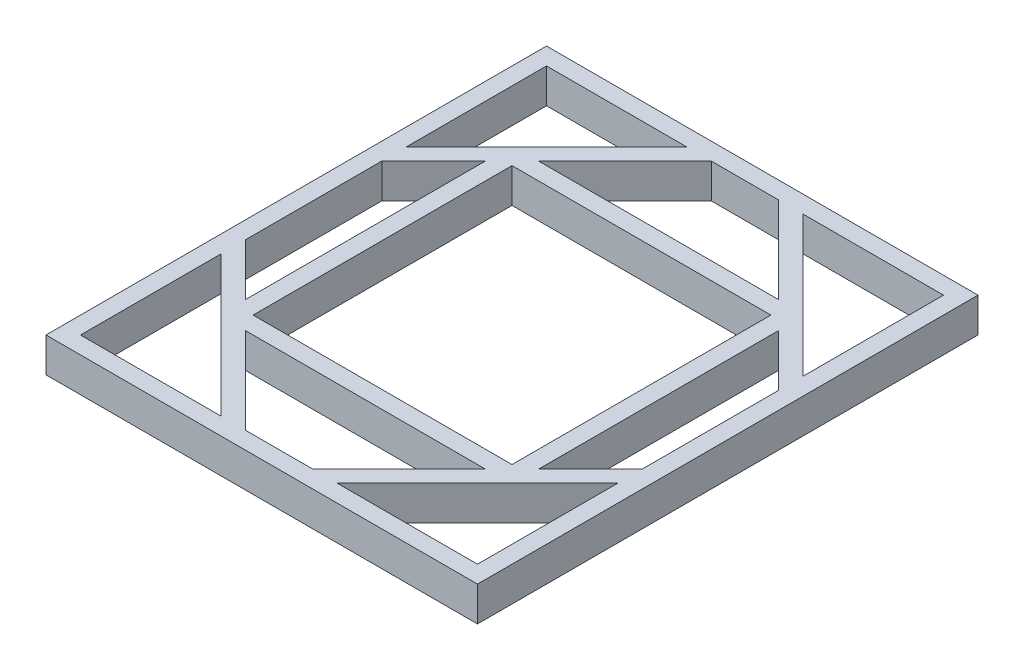
SolidWorks part; units mm, degrees
ref_plane "Front Plane" through (0, 0, 0) normal (0, 0, 1) x (1, 0, 0)
ref_plane "Top Plane" through (0, 0, 0) normal (0, 1, 0) x (1, 0, 0)
ref_plane "Right Plane" through (0, 0, 0) normal (1, 0, 0) x (0, 0, -1)
sketch "Sketch1" plane through (0, 0, 0) normal (0, 1, 0) x (1, 0, 0)
  line L0 (-292.1, 136.3541) -> (-85.5541, 342.9)
  line L1 (-317.5, -368.3) -> (317.5, -368.3)
  line L2 (-317.5, -368.3) -> (-317.5, 368.3)
  line L3 (-317.5, 368.3) -> (317.5, 368.3)
  line L4 (317.5, -368.3) -> (317.5, 368.3)
  line L5 (-317.5, -368.3) -> (317.5, 368.3) construction
  line L6 (-317.5, 368.3) -> (317.5, -368.3) construction
  line L7 (-292.1, -342.9) -> (292.1, -342.9)
  line L8 (-292.1, -342.9) -> (-292.1, 342.9)
  line L9 (-292.1, 342.9) -> (292.1, 342.9)
  line L10 (292.1, -342.9) -> (292.1, 342.9)
  line L11 (-292.1, -342.9) -> (292.1, 342.9) construction
  line L12 (-292.1, 342.9) -> (292.1, -342.9) construction
  line L13 (-292.1, 100.4331) -> (-49.6331, 342.9)
  line L14 (0, 342.9) -> (0, -342.9) construction
  line L15 (-274.1395, 118.3936) -> (-67.5936, 324.9395) construction
  line L16 (-292.1, 0) -> (292.1, 0) construction
  line L17 (292.1, 100.4331) -> (49.6331, 342.9)
  line L18 (292.1, 136.3541) -> (85.5541, 342.9)
  line L19 (292.1, -100.4331) -> (49.6331, -342.9)
  line L20 (292.1, -136.3541) -> (85.5541, -342.9)
  line L21 (-292.1, -100.4331) -> (-49.6331, -342.9)
  line L22 (-292.1, -136.3541) -> (-85.5541, -342.9)
  line L23 (-215.9, 176.6331) -> (-215.9, -176.6331)
  line L24 (-190.5, 202.0331) -> (-190.5, -202.0331)
  line L25 (-202.057, 190.4761) -> (202.057, 190.4761)
  line L26 (-176.657, 215.8761) -> (176.657, 215.8761)
  line L27 (-202.057, -190.4761) -> (202.057, -190.4761)
  line L28 (-176.657, -215.8761) -> (176.657, -215.8761)
  line L29 (190.5, 202.0331) -> (190.5, -202.0331)
  line L30 (215.9, 176.6331) -> (215.9, -176.6331)
  point P0 (0, 0)
  point P6 (0, 0)
  dimension "D1" = 635
  dimension "D2" = 736.6
  dimension "D3" = 685.8
  dimension "D4" = 584.2
  dimension "D5" = 135
  dimension "D6" = 292.1
  dimension "D8" = 76.2
  dimension "D9" = 25.4
  dimension "D10" = 404.114
  dimension "D11" = 25.4
  dimension "D7" = 25.4
extrude "Boss-Extrude1" add sketch "Sketch1" along normal blind 50.8 contours L8 L22 L7 L21 | L8 L13 L9 L0 | L10 L18 L9 L17 | L20 L10 L19 L7 | L1 L4 L3 L2 L10 L7 L8 L9 | L29 L17 L26 L13 L24 L25 | L21 L27 L24 L25 L13 L23 | L30 L17 L25 L29 L27 L19 | L29 L27 L24 L21 L28 L19 | L13 L25 L24 | L27 L21 L24 | L27 L29 L19 | L17 L29 L25
sketch "Sketch2" plane through (0, 50.8, 0) normal (0, 1, 0) x (1, 0, 0)
  line L0 (0, -368.3) -> (0, 368.3) construction
  line L1 (-317.5, -368.3) -> (317.5, -368.3) construction
  line L2 (-317.5, 368.3) -> (317.5, 368.3) construction
  line L3 (-177.8, 368.3) -> (-177.8, -368.3)
  line L4 (-184.15, 368.3) -> (-184.15, -368.3)
  line L5 (-214.122, 368.3) -> (-214.122, -368.3)
  line L6 (-245.872, 368.3) -> (-245.872, -368.3)
  line L7 (-226.822, -368.3) -> (-201.422, -368.3)
  line L8 (-226.822, -368.3) -> (-226.822, 368.3)
  line L9 (-226.822, 368.3) -> (-201.422, 368.3)
  line L10 (-201.422, -368.3) -> (-201.422, 368.3)
  line L11 (-226.822, -368.3) -> (-201.422, 368.3) construction
  line L12 (-226.822, 368.3) -> (-201.422, -368.3) construction
  point P12 (-214.122, 0)
  dimension "D1" = 177.8
  dimension "D2" = 6.35
  dimension "D3" = 29.972
  dimension "D4" = 12.7
  dimension "D5" = 31.75
